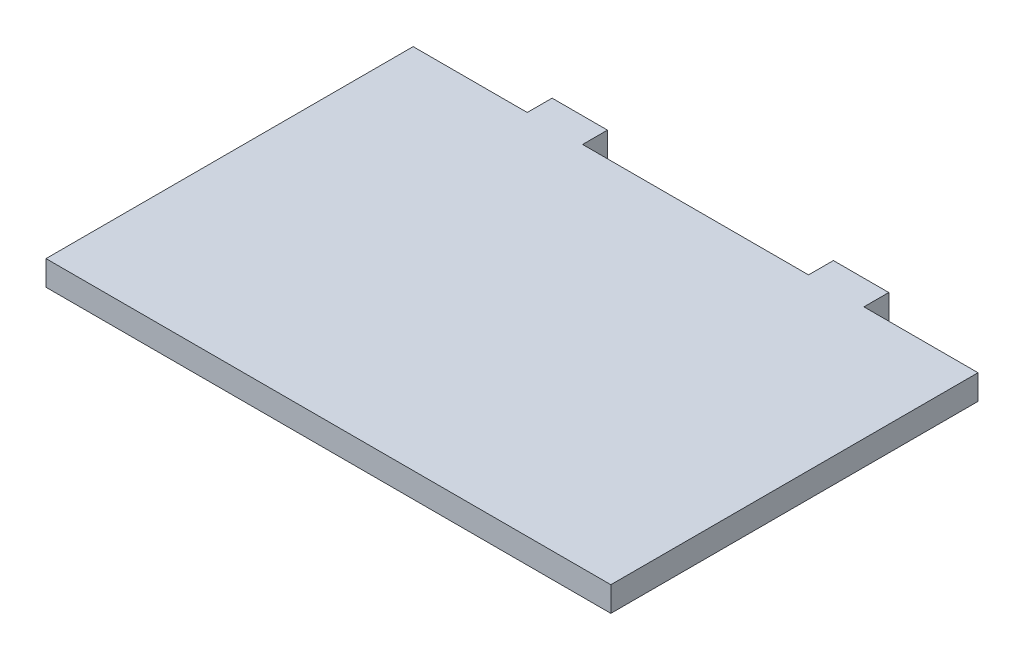
SolidWorks part; units mm, degrees
ref_plane "Front Plane" through (0, 0, 0) normal (0, 0, 1) x (1, 0, 0)
ref_plane "Top Plane" through (0, 0, 0) normal (0, 1, 0) x (1, 0, 0)
ref_plane "Right Plane" through (0, 0, 0) normal (1, 0, 0) x (0, 0, -1)
sketch "Sketch1" plane through (0, 0, 0) normal (0, 1, 0) x (1, 0, 0)
  line L1 (-63.5, -41.275) -> (63.5, -41.275)
  line L2 (-63.5, -41.275) -> (-63.5, 41.275)
  line L3 (-63.5, 41.275) -> (-37.846, 41.275)
  line L4 (63.5, -41.275) -> (63.5, 41.275)
  line L5 (-63.5, -41.275) -> (63.5, 41.275) construction
  line L6 (-63.5, 41.275) -> (63.5, -41.275) construction
  line L14 (-63.5, 0) -> (63.5, 0) construction
  line L15 (37.846, 46.863) -> (37.846, 41.275)
  line L16 (25.4, 46.863) -> (37.846, 46.863)
  line L17 (25.4, 41.275) -> (25.4, 46.863)
  line L18 (-25.4, 46.863) -> (-25.4, 41.275)
  line L19 (-37.846, 46.863) -> (-25.4, 46.863)
  line L20 (-37.846, 41.275) -> (-37.846, 46.863)
  line L21 (-25.4, 41.275) -> (25.4, 41.275)
  line L22 (37.846, 41.275) -> (63.5, 41.275)
  point P0 (0, 0)
  dimension "D1" = 127
  dimension "D2" = 82.55
  dimension "D3" = 12.446
  dimension "D4" = 5.588
  dimension "D5" = 50.8
extrude "Boss-Extrude1" add sketch "Sketch1" along normal blind 5.588
